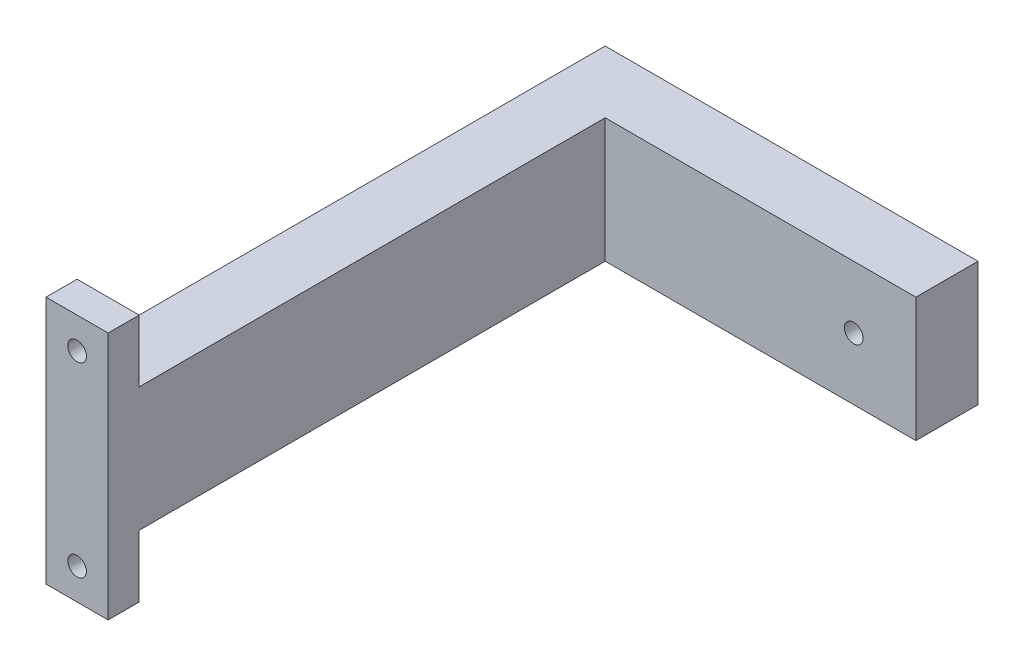
SolidWorks part; units mm, degrees
ref_plane "Ön Düzlem" through (0, 0, 0) normal (0, 0, 1) x (1, 0, 0)
ref_plane "Üst Düzlem" through (0, 0, 0) normal (0, 1, 0) x (1, 0, 0)
ref_plane "Sağ Düzlem" through (0, 0, 0) normal (1, 0, 0) x (0, 0, -1)
sketch "Çizim1" plane through (0, 0, 0) normal (0, 1, 0) x (1, 0, 0)
  line L0 (-10, 0) -> (0, 0)
  line L3 (0, 0) -> (0, 80)
  line L4 (0, 80) -> (50, 80)
  line L5 (50, 80) -> (50, 90)
  line L6 (50, 90) -> (-10, 90)
  line L7 (-10, 90) -> (-10, 0)
  point P0 (0, 0)
  point P3 (0, 0)
  point P10 (0, 0)
  dimension "D1" = 10
  dimension "D2" = 10
  dimension "D3" = 50
  dimension "D4" = 90
extrude "Yükseklik-Ekstrüzyon1" add sketch "Çizim1" along normal blind 20
sketch "Çizim2" plane through (0, 20, 0) normal (0, 1, 0) x (1, 0, 0)
  line L0 (0, 0) -> (0, 80) construction
  line L1 (-10, 0) -> (0, 0)
  line L2 (-10, 0) -> (-10, 5)
  line L3 (-10, 5) -> (0, 5)
  line L4 (0, 0) -> (0, 5)
  dimension "D1" = 5
extrude "Yükseklik-Ekstrüzyon2" add sketch "Çizim2" along normal blind 10 and the other way blind 30
sketch "Çizim3" plane through (0, 0, -5) normal (0, 0, -1) x (-1, 0, 0)
  line L0 (0, 30) -> (10, 30) construction
  circle A0 centre (5, 25) radius 1.5
  circle A1 centre (5, -5) radius 1.5
  point P4 (0, 0)
  point P8 (12.9888, -8.1762)
  dimension "D1" = 3
  dimension "D2" = 5
  dimension "D3" = 5
  dimension "D4" = 5
extrude "Kes-Ekstrüzyon1" cut sketch "Çizim3" against normal blind 10
sketch "Çizim4" plane through (0, 0, -90) normal (0, 0, -1) x (-1, 0, 0)
  line L0 (-50, 20) -> (-50, 0) construction
  line L1 (-50, 0) -> (10, 0) construction
  circle A0 centre (-40, 10) radius 1.5
  dimension "D1" = 3
  dimension "D2" = 10
  dimension "D3" = 10
extrude "Kes-Ekstrüzyon2" cut sketch "Çizim4" against normal blind 10
